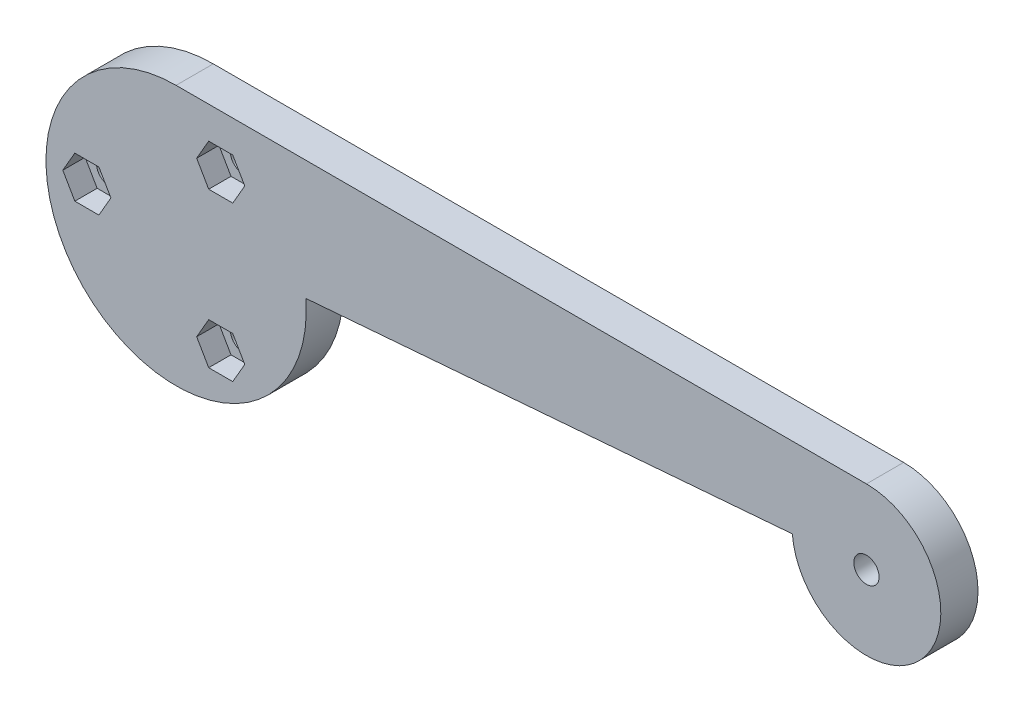
SolidWorks part; units mm, degrees
ref_plane "Front Plane" through (0, 0, 0) normal (0, 0, 1) x (1, 0, 0)
ref_plane "Top Plane" through (0, 0, 0) normal (0, 1, 0) x (1, 0, 0)
ref_plane "Right Plane" through (0, 0, 0) normal (1, 0, 0) x (0, 0, -1)
sketch "Sketch1" plane through (0, 0, 0) normal (0, 0, 1) x (1, 0, 0)
  line L0 (0, 0) -> (90, 0) construction
  line L1 (0, 17.5) -> (92.8257, 17.5)
  line L2 (17.4432, 1.4093) -> (82.8582, 6.6947)
  line L3 (82.8582, 6.6947) -> (82.6496, 9.2766) construction
  line L4 (17.4432, 1.4093) -> (16.6278, 11.5008) construction
  arc A0 (0, 17.5) -> (17.4432, 1.4093) centre (0, 0) ccw
  arc A1 (92.8257, 17.5) -> (82.8582, 6.6947) centre (92.8257, 7.5) cw
  dimension "D1" = 17.5
  dimension "D3" = 10
  dimension "D2" = 90
  dimension "D4" = 90
  dimension "D5" = 90
extrude "Boss-Extrude1" add sketch "Sketch1" along normal blind 5
hole_wizard "M3 Clearance Hole1" positions "Sketch6" profile "Sketch7" hole size "M3" standard "ISO" end condition through all
sketch "Sketch6" plane through (0, 0, 5) normal (0, 0, 1) x (1, 0, 0)
  point P0 (-12, 0)
  dimension "D1" = 12
sketch "Sketch7" plane through (-12, 0, 5) normal (1, 0, 0) x (0, -1, 0)
  line L0 (0, 0) -> (0, 5)
  line L1 (0, 5) -> (1.7, 5)
  line L2 (1.7, 5) -> (1.7, 0)
  line L5 (1.7, 0) -> (0, 0)
  line L11 (0, -6.35) -> (0, 107.95) construction
  dimension "Thru Hole Dia." = 3.4
  dimension "Thru Hole Depth" = 5
sketch "Sketch8" plane through (0, 0, 5) normal (0, 0, 1) x (1, 0, 0)
  line L1 (-10.3834, 2.8) -> (-13.6166, 2.8)
  line L2 (-13.6166, 2.8) -> (-15.2332, 0)
  line L3 (-15.2332, 0) -> (-13.6166, -2.8)
  line L4 (-13.6166, -2.8) -> (-10.3834, -2.8)
  line L5 (-10.3834, -2.8) -> (-8.7668, 0)
  line L6 (-8.7668, 0) -> (-10.3834, 2.8)
  circle A0 centre (-12, 0) radius 2.8 construction
  dimension "D1" = 5.6
extrude "Cut-Extrude1" cut sketch "Sketch8" against normal blind 3
pattern_circular "CirPattern1" count 3 over 360 about axis through (0, 0, 0) along (0, 0, 1) of "Cut-Extrude1", "M3 Clearance Hole1"
hole_wizard "M3 Clearance Hole2" positions "Sketch10" profile "Sketch11" hole size "M3" standard "ISO" end condition through all
sketch "Sketch10" plane through (0, 0, 5) normal (0, 0, 1) x (1, 0, 0)
  point P11 (92.8257, 7.5)
sketch "Sketch11" plane through (92.8257, 7.5, 5) normal (1, 0, 0) x (0, -1, 0)
  line L0 (0, 0) -> (0, 5)
  line L1 (0, 5) -> (1.7, 5)
  line L2 (1.7, 5) -> (1.7, 0)
  line L5 (1.7, 0) -> (0, 0)
  line L11 (0, -6.35) -> (0, 107.95) construction
  dimension "Thru Hole Dia." = 3.4
  dimension "Thru Hole Depth" = 5
